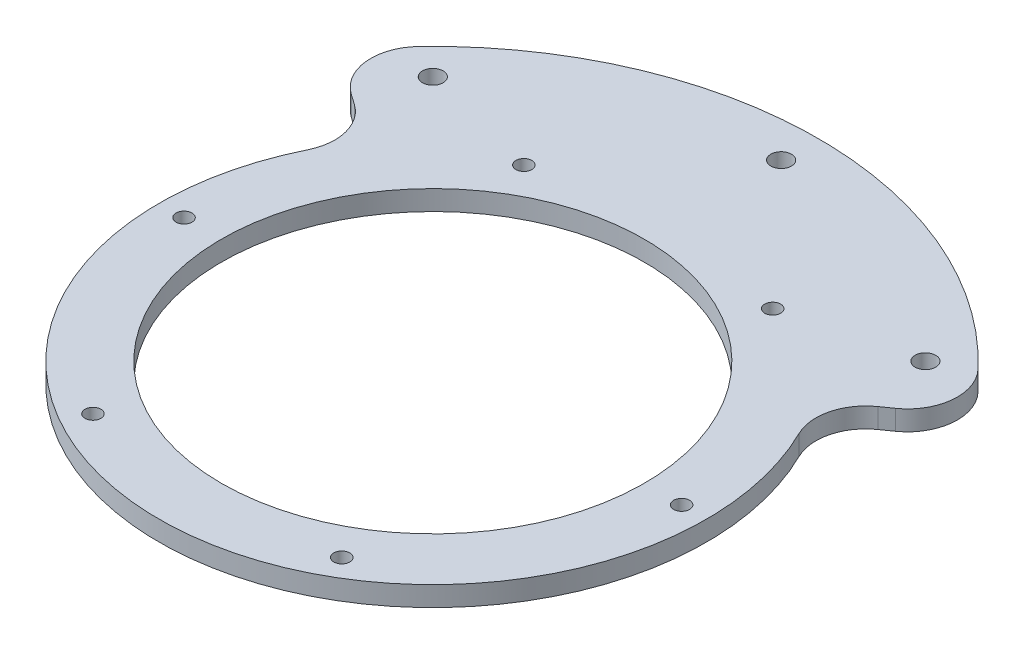
SolidWorks part; units mm, degrees
ref_plane "前视基准面" through (0, 0, 0) normal (0, 0, 1) x (1, 0, 0)
ref_plane "上视基准面" through (0, 0, 0) normal (0, 1, 0) x (1, 0, 0)
ref_plane "右视基准面" through (0, 0, 0) normal (1, 0, 0) x (0, 0, -1)
sketch "草图1" plane through (0, 0, 0) normal (0, 1, 0) x (1, 0, 0)
  line L0 (0, 0) -> (0, 81.5111) construction
  line L1 (0, 0) -> (-49.4975, 49.4975) construction
  line L2 (0, 0) -> (-63.4843, 44.4522)
  line L3 (0, 0) -> (63.4843, 44.4522)
  circle A6 centre (0, 0) radius 50 construction
  circle A7 centre (25, 43.3013) radius 1.6
  circle A8 centre (50, 0) radius 1.6
  circle A9 centre (25, -43.3013) radius 1.6
  circle A10 centre (-25, -43.3013) radius 1.6
  circle A11 centre (-50, 0) radius 1.6
  circle A12 centre (-25, 43.3013) radius 1.6
  circle A13 centre (0, 0) radius 55
  circle A20 centre (0, 0) radius 42.5
  circle A21 centre (0, 0) radius 70 construction
  circle A22 centre (0, 70) radius 2.075
  circle A23 centre (-49.4975, 49.4975) radius 2.075
  circle A24 centre (49.4975, 49.4975) radius 2.075
  circle A25 centre (0, 0) radius 77.5
  dimension "D2" = 85
  dimension "D3" = 140
  dimension "D4" = 4.15
  dimension "D6" = 155
  dimension "D7" = 6
  dimension "D5" = 45
  dimension "D8" = 3.2
  dimension "D9" = 50
  dimension "D10" = 110
  dimension "D11" = 10
extrude "凸台-拉伸1" add sketch "草图1" along normal blind 4 contours L3 A25 L2 A13 A24 A23 A22 | A20 L3 A13 L2 A7 A12 | A20 L2 A13 L3 A8 A9 A10 A11
fillet "圆角1" radius 10 4 edges at (-63.4843, 2, -44.4522) (-45.0534, 2, -31.5467) (63.4843, 2, -44.4522) (45.0534, 2, -31.5467)
